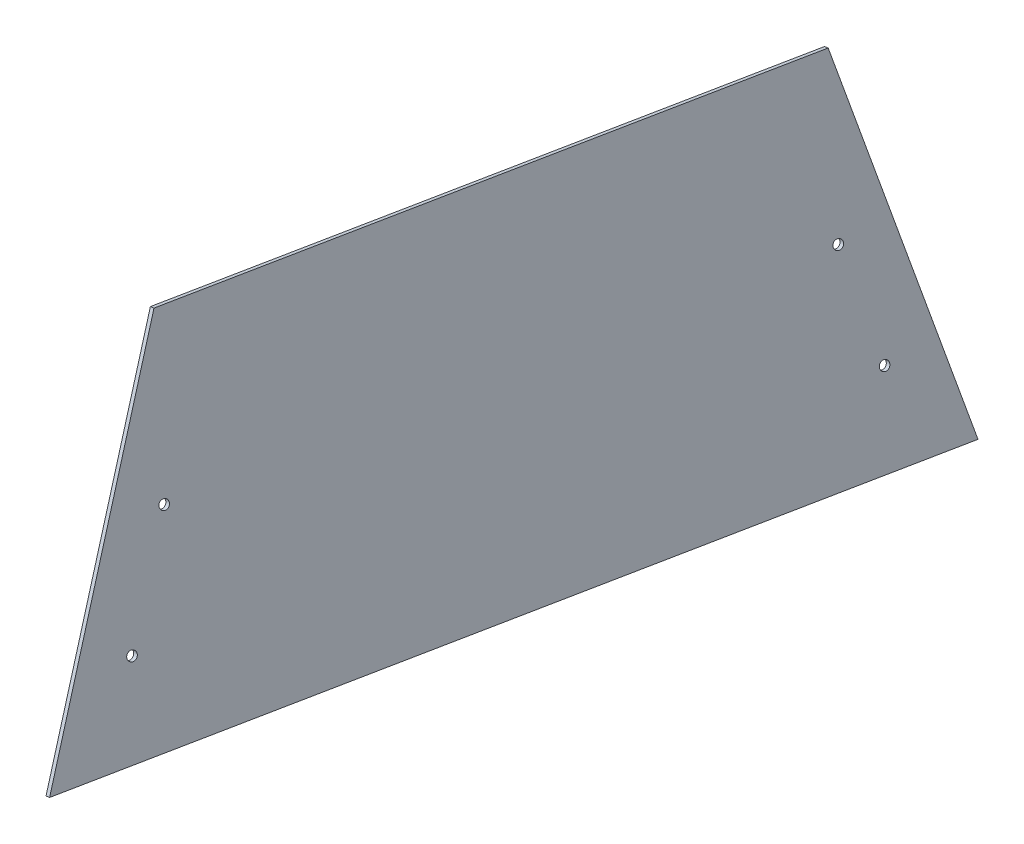
SolidWorks part; units mm, degrees
material "Thornel VCB-20 Carbon Cloth"
ref_plane "Front Plane" through (0, 0, 0) normal (0, 0, 1) x (1, 0, 0)
ref_plane "Top Plane" through (0, 0, 0) normal (0, 1, 0) x (1, 0, 0)
ref_plane "Right Plane" through (0, 0, 0) normal (1, 0, 0) x (0, 0, -1)
ref_plane "Plane1" through (661.4861, 211.2284, 131.5661) normal (0.936, 0.2989, 0.1862) x (0.1773, 0.0566, -0.9825)
sketch "Sketch1" plane through (661.4861, 211.2284, 131.5661) normal (0.936, 0.2989, 0.1862) x (0.1773, 0.0566, -0.9825)
  line L0 (-1711.561, 536.5838) -> (-1818.359, 342.5793)
  line L1 (-1818.359, 342.5793) -> (-1328.6611, 313.4694)
  line L2 (-1328.6611, 313.4694) -> (-1355.9566, 515.445)
  line L3 (-1355.9566, 515.445) -> (-1711.561, 536.5838)
  line L4 (-1428.3419, 1051.0671) -> (-1868.8378, 250.8817) construction
  line L5 (-1428.3419, 1051.0671) -> (-1321.2913, 258.9362) construction
  line L6 (-1764.96, 439.5815) -> (-1342.3088, 414.4572) construction
  line L7 (-1589.6785, 757.9902) -> (-1387.1074, 745.9484) construction
  point P8 (-1764.96, 439.5815)
  point P9 (-1711.5366, 536.6281)
  dimension "D1" = 200
  dimension "D2" = 75
extrude "Boss-Extrude1" add sketch "Sketch1" along normal blind 3
sketch "Sketch3" plane through (661.4861, 211.2284, 131.5661) normal (0.936, 0.2989, 0.1862) x (0.1773, 0.0566, -0.9825)
  line L0 (-1373.0164, 365.0786) -> (-1357.5437, 364.1588) construction
  line L1 (-1365.9854, 426.624) -> (-1381.4581, 427.5438) construction
  line L2 (-1737.0139, 448.6797) -> (-1721.5412, 447.7599) construction
  line L3 (-1769.9818, 388.676) -> (-1754.5091, 387.7563) construction
  circle A0 centre (-1729.2776, 448.2198) radius 2.75
  circle A1 centre (-1762.2454, 388.2161) radius 2.75
  circle A2 centre (-1365.2801, 364.6187) radius 2.75
  circle A3 centre (-1373.7218, 427.0839) radius 2.75
  arc A4 (-1370.1081, 367.6605) -> (-1370.4344, 362.1702) centre (-1370.2712, 364.9154) ccw construction
  arc A5 (-1360.4521, 361.5768) -> (-1360.1257, 367.0671) centre (-1360.2889, 364.322) ccw construction
  arc A6 (-1368.8938, 424.0421) -> (-1368.5674, 429.5324) centre (-1368.7306, 426.7872) ccw construction
  arc A7 (-1378.5498, 430.1258) -> (-1378.8761, 424.6355) centre (-1378.713, 427.3806) ccw construction
  arc A8 (-1734.1056, 451.2617) -> (-1734.4319, 445.7713) centre (-1734.2688, 448.5165) ccw construction
  arc A9 (-1724.4496, 445.178) -> (-1724.1232, 450.6683) centre (-1724.2864, 447.9231) ccw construction
  arc A10 (-1767.0734, 391.258) -> (-1767.3998, 385.7677) centre (-1767.2366, 388.5128) ccw construction
  arc A11 (-1757.4174, 385.1743) -> (-1757.0911, 390.6646) centre (-1757.2542, 387.9194) ccw construction
  dimension "D1" = 5.5
  dimension "D2" = 5.5
  dimension "D3" = 5.5
  dimension "D4" = 5.5
extrude "Cut-Extrude1" cut sketch "Sketch3" against normal through all both and the other way through all
